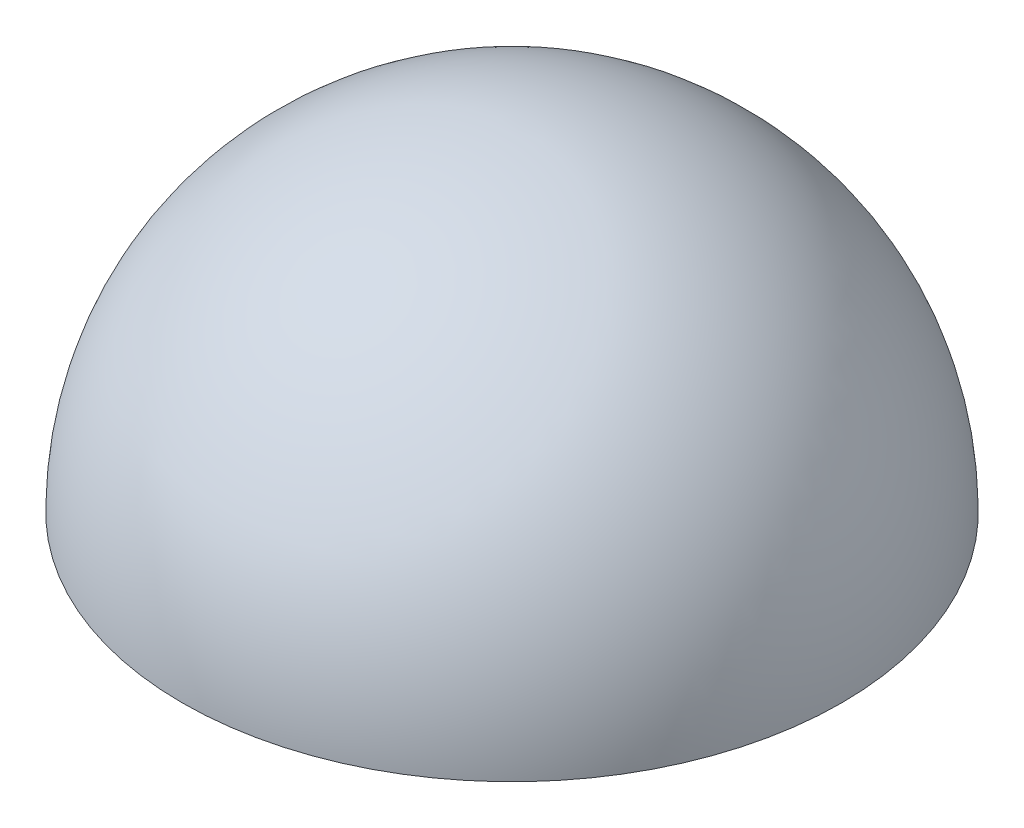
SolidWorks part; units mm, degrees
ref_plane "前视基准面" through (0, 0, 0) normal (0, 0, 1) x (1, 0, 0)
ref_plane "上视基准面" through (0, 0, 0) normal (0, 1, 0) x (1, 0, 0)
ref_plane "右视基准面" through (0, 0, 0) normal (1, 0, 0) x (0, 0, -1)
sketch "草图1" plane through (0, 0, 0) normal (0, 0, 1) x (1, 0, 0)
  line L0 (0, 40) -> (0, 37.5)
  line L1 (0, -37.5) -> (0, -40)
  arc A0 (0, -37.5) -> (0, 37.5) centre (0, 0) ccw
  arc A1 (0, -40) -> (0, 40) centre (0, 0) ccw
  dimension "D1" = 80
  dimension "D2" = 75
revolve "旋转1" add sketch "草图1" angle 360 about L0
sketch "草图2" plane through (0, 0, 0) normal (0, 1, 0) x (1, 0, 0)
  circle A0 centre (0, 0) radius 46.1834
extrude "切除-拉伸1" cut sketch "草图2" against normal blind 500
